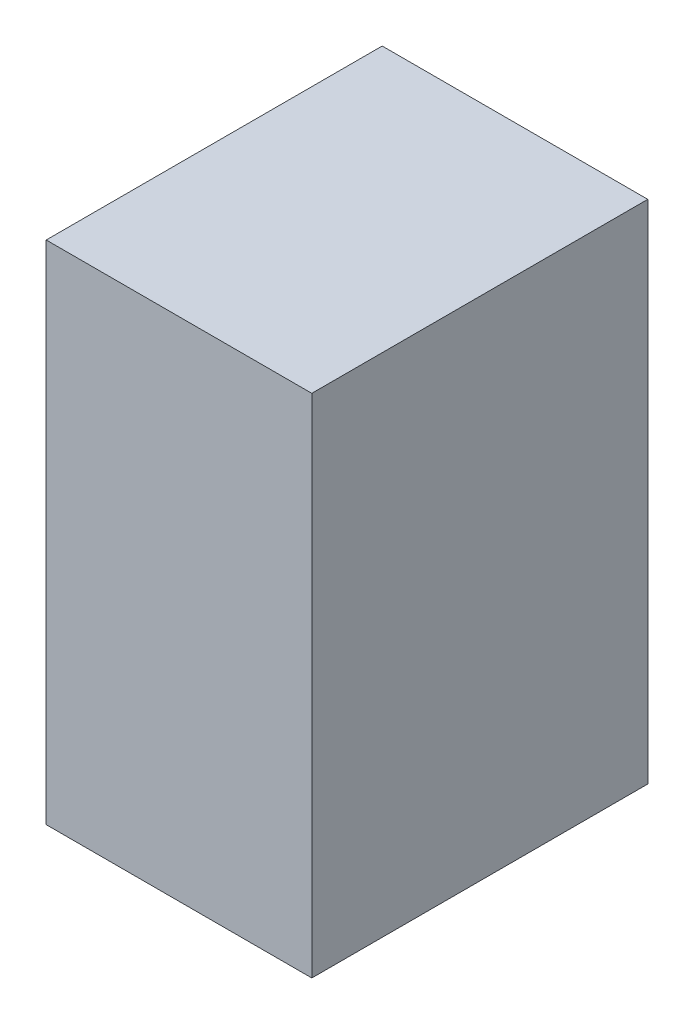
SolidWorks part; units mm, degrees
ref_plane "Front Plane" through (0, 0, 0) normal (0, 0, 1) x (1, 0, 0)
ref_plane "Top Plane" through (0, 0, 0) normal (0, 1, 0) x (1, 0, 0)
ref_plane "Right Plane" through (0, 0, 0) normal (1, 0, 0) x (0, 0, -1)
ref_plane "Plane1" through (0, 0, 110) normal (0, 0, 1) x (1, 0, 0)
ref_plane "Plane2" through (0, 0, 120) normal (0, 0, 1) x (1, 0, 0)
sketch "Sketch3" plane through (0, 0, 120) normal (0, 0, 1) x (1, 0, 0)
  line L5 (-655.6809, -1276.1699) -> (-694.681, -1276.1699) construction
  line L6 (-692.931, -1278.4199) -> (-657.431, -1278.4199) construction
  line L10 (-692.931, -1278.4199) -> (-692.931, -1326.9199) construction
  line L11 (-692.931, -1326.9199) -> (-657.431, -1326.9199) construction
  line L12 (-657.431, -1278.4199) -> (-657.431, -1326.9199) construction
  line L13 (-692.931, -1278.4199) -> (-657.431, -1326.9199) construction
  line L14 (-692.931, -1326.9199) -> (-657.431, -1278.4199) construction
  line L15 (-687.681, -1329.1699) -> (-662.681, -1329.1699)
  line L16 (-687.681, -1329.1699) -> (-687.681, -1276.1699)
  line L17 (-687.681, -1276.1699) -> (-662.681, -1276.1699)
  line L18 (-662.681, -1329.1699) -> (-662.681, -1276.1699)
  line L19 (-687.681, -1329.1699) -> (-662.681, -1276.1699) construction
  line L20 (-687.681, -1276.1699) -> (-662.681, -1329.1699) construction
  line L22 (-681.431, -1322.6699) -> (-668.931, -1322.6699)
  line L23 (-681.431, -1322.6699) -> (-681.431, -1282.6699)
  line L24 (-681.431, -1282.6699) -> (-668.931, -1282.6699)
  line L25 (-668.931, -1322.6699) -> (-668.931, -1282.6699)
  line L26 (-681.431, -1322.6699) -> (-668.931, -1282.6699) construction
  line L27 (-681.431, -1282.6699) -> (-668.931, -1322.6699) construction
  point P4 (-675.181, -1302.6699)
  point P7 (-675.181, -1302.6699)
  point P14 (-675.181, -1302.6699)
  dimension "D1" = 25
  dimension "D2" = 12.5
  dimension "D3" = 40
extrude "Boss-Extrude1" add sketch "Sketch3" against normal up to surface (120 mm away)
sketch "Sketch4" plane through (0, 0, 120) normal (0, 0, 1) x (1, 0, 0)
  line L0 (-675.181, -1329.1699) -> (-675.181, -1276.1699) construction
  line L1 (-687.681, -1329.1699) -> (-662.681, -1329.1699) construction
  line L2 (-662.681, -1276.1699) -> (-687.681, -1276.1699) construction
  line L3 (-662.681, -1302.6699) -> (-687.681, -1302.6699) construction
  line L4 (-662.681, -1329.1699) -> (-662.681, -1276.1699) construction
  line L5 (-687.681, -1276.1699) -> (-687.681, -1329.1699) construction
  line L6 (-696.431, -1323.4199) -> (-696.431, -1281.9199) construction
  line L7 (-633.931, -1256.1699) -> (-716.431, -1256.1699)
  line L8 (-633.931, -1256.1699) -> (-633.931, -1349.1699)
  line L9 (-633.931, -1349.1699) -> (-716.431, -1349.1699)
  line L10 (-716.431, -1256.1699) -> (-716.431, -1349.1699)
  line L11 (-633.931, -1256.1699) -> (-716.431, -1349.1699) construction
  line L12 (-633.931, -1349.1699) -> (-716.431, -1256.1699) construction
  point P12 (-675.181, -1302.6699)
  dimension "D1" = 20
  dimension "D2" = 20
extrude "Boss-Extrude2" add sketch "Sketch4" against normal blind 10
sketch "Sketch5" plane through (-687.681, 0, 0) normal (-1, 0, 0) x (0, 0, 1)
  line L8 (-3.81, -1276.1699) -> (0, -1276.1699)
  line L13 (-3.81, -1276.1699) -> (-3.81, -1271.1699)
  line L14 (0, -1272.1699) -> (0, -1271.1699)
  line L19 (-3.81, -1271.1699) -> (0, -1271.1699)
  line L20 (0, -1276.1699) -> (0, -1280.1699)
  line L21 (4, -1276.1699) -> (7.5, -1276.1699)
  line L25 (0, -1280.1699) -> (7.5, -1280.1699)
  line L26 (7.5, -1276.1699) -> (7.5, -1280.1699)
  line L27 (-6.25, -1302.6699) -> (13.6345, -1302.6699) construction
  line L28 (-6.25, -1289.5199) -> (-6.25, -1315.8199) construction
  line L29 (7.5, -1329.1699) -> (7.5, -1325.1699)
  line L30 (0, -1325.1699) -> (7.5, -1325.1699)
  line L31 (4, -1329.1699) -> (7.5, -1329.1699)
  line L32 (0, -1329.1699) -> (0, -1325.1699)
  line L33 (-3.81, -1334.1699) -> (0, -1334.1699)
  line L34 (0, -1333.1699) -> (0, -1334.1699)
  line L35 (-3.81, -1329.1699) -> (-3.81, -1334.1699)
  line L36 (-3.81, -1329.1699) -> (0, -1329.1699)
  arc A2 (4, -1276.1699) -> (0, -1272.1699) centre (4, -1272.1699) cw
  arc A3 (4, -1329.1699) -> (0, -1333.1699) centre (4, -1333.1699) ccw
  dimension "D2" = 7.5
  dimension "D3" = 5
  dimension "D1" = 4
extrude "Boss-Extrude3" add sketch "Sketch5" against normal up to surface (25 mm away) up to face at (-662.681, -1302.6699, 55)
sketch "Sketch6" plane through (-738.361, 0, 0) normal (-1, 0, 0) x (0, 0, 1)
  line L0 (120, -1256.1699) -> (120, -1349.1699) construction
  line L9 (120, -1256.1699) -> (120, -1349.1699)
  line L10 (120, -1256.1699) -> (-5, -1256.1699)
  line L11 (120, -1349.1699) -> (-5, -1349.1699)
  line L12 (-5, -1256.1699) -> (-5, -1349.1699)
  circle A0 centre (79.5065, -1302.8998) radius 32.5 construction
  circle A3 centre (79.5065, -1302.8998) radius 35
  dimension "D1" = 2.5
  dimension "D2" = 46.2701
  dimension "D4" = 70
  dimension "D3" = 40.4935
  dimension "D5" = 125
sketch "Sketch10" plane through (-687.681, 0, 0) normal (-1, 0, 0) x (0, 0, 1)
  circle A0 centre (0, -1329.1699) radius 0.5
  circle A1 centre (0, -1276.1699) radius 0.5
  dimension "D1" = 1
extrude "Cut-Extrude1" cut sketch "Sketch10" against normal through all both and the other way through all
sketch "Sketch11" plane through (0, -1256.1699, 0) normal (0, 1, 0) x (1, 0, 0)
  line L13 (-687.681, 3.81) -> (-662.681, 3.81)
  line L14 (-687.681, 3.81) -> (-687.681, 0)
  line L15 (-687.681, 0) -> (-662.681, 0)
  line L16 (-662.681, 3.81) -> (-662.681, 0)
  line L17 (-687.681, 3.81) -> (-662.681, 0) construction
  line L18 (-687.681, 0) -> (-662.681, 3.81) construction
  point P18 (-675.181, 1.905)
extrude "Boss-Extrude11" add sketch "Sketch11" against normal up to surface (15 mm away) up to face at (-675.181, -1271.1699, -1.905)
sketch "Sketch12" plane through (0, -1256.1699, 0) normal (0, 1, 0) x (1, 0, 0)
  line L1 (-710.761, 12.5) -> (-707.761, 12.5)
  line L2 (-710.761, 12.5) -> (-710.761, -30.4539)
  line L3 (-710.761, -30.4539) -> (-707.761, -30.4539)
  line L4 (-707.761, 12.5) -> (-707.761, -30.4539)
  line L5 (-710.761, 12.5) -> (-707.761, -30.4539) construction
  line L6 (-710.761, -30.4539) -> (-707.761, 12.5) construction
  line L7 (-642.6009, 12.5) -> (-639.6009, 12.5)
  line L8 (-642.6009, 12.5) -> (-642.6009, -25.4539)
  line L9 (-642.6009, -25.4539) -> (-639.6009, -25.4539)
  line L10 (-639.6009, 12.5) -> (-639.6009, -25.4539)
  line L11 (-642.6009, 12.5) -> (-639.6009, -25.4539) construction
  line L12 (-642.6009, -25.4539) -> (-639.6009, 12.5) construction
  point P4 (-709.261, -8.9769)
  point P11 (-641.1009, -6.4769)
extrude "Boss-Extrude12" add sketch "Sketch12" against normal up to surface (24 mm away) separate body
sketch "Sketch13" plane through (0, -1256.1699, 0) normal (0, 1, 0) x (1, 0, 0)
  line L0 (-652.1809, 30.41) -> (-698.1809, 30.41) construction
  line L1 (-695.2818, 35.57) -> (-655.0818, 35.57)
  line L2 (-695.2818, 35.57) -> (-695.2818, 30.41)
  line L3 (-695.2818, 30.41) -> (-655.0818, 30.41)
  line L4 (-655.0818, 35.57) -> (-655.0818, 30.41)
  line L5 (-695.2818, 35.57) -> (-655.0818, 30.41) construction
  line L6 (-695.2818, 30.41) -> (-655.0818, 35.57) construction
  point P4 (-675.1818, 32.99)
  dimension "D1" = 20.1
extrude "Boss-Extrude13" add sketch "Sketch13" against normal up to surface (10.4024 mm away) separate body
sketch "Sketch14" plane through (0, -1256.1699, 0) normal (0, 1, 0) x (1, 0, 0)
  line L0 (-716.431, -120) -> (-633.931, -120)
  line L1 (-716.431, -120) -> (-716.431, 35.5)
  line L2 (-633.931, -120) -> (-633.931, 35.5)
  line L3 (-716.431, 35.5) -> (-633.931, 35.5)
  dimension "D1" = 155.5
extrude "Boss-Extrude14" add sketch "Sketch14" against normal blind 5
sketch "Sketch15" plane through (-738.361, 0, 0) normal (-1, 0, 0) x (0, 0, 1)
  line L2 (120, -1349.1699) -> (-35.5, -1349.1699)
  line L3 (120, -1349.1699) -> (120, -1256.1699)
  line L4 (120, -1256.1699) -> (-35.5, -1256.1699)
  line L5 (-35.5, -1349.1699) -> (-35.5, -1256.1699)
  line L6 (120, -1349.1699) -> (-35.5, -1256.1699) construction
  line L7 (120, -1256.1699) -> (-35.5, -1349.1699) construction
  circle A0 centre (69.5065, -1302.44) radius 37.4
  circle A1 centre (69.5065, -1302.44) radius 30 construction
  point P9 (42.25, -1302.6699)
  dimension "D1" = 7.4
extrude "Boss-Extrude15" add sketch "Sketch15" along normal blind 20 separate body
sketch "Sketch16" plane through (-716.431, 0, 0) normal (-1, 0, 0) x (0, 0, 1)
  line L0 (110, -1349.1699) -> (120, -1349.1699)
  line L1 (120, -1349.1699) -> (120, -1256.1699)
  line L2 (120, -1256.1699) -> (-35.5, -1256.1699)
  line L3 (110, -1349.1699) -> (110, -1261.1699)
  line L4 (110, -1261.1699) -> (-35.5, -1261.1699)
  line L5 (-35.5, -1256.1699) -> (-35.5, -1349.1699) construction
  line L6 (-35.5, -1261.1699) -> (-35.5, -1256.1699)
  dimension "D1" = 5
extrude "Boss-Extrude16" add sketch "Sketch16" along normal up to surface (21.93 mm away) up to face at (-738.361, -1302.6699, 42.25)
extrude "Boss-Extrude4" add sketch "Sketch6" along normal blind 25 separate body
sketch "Sketch7" plane through (-103.987, 0, 0) normal (-1, 0, 0) x (0, 0, 1)
  line L1 (922.519, -46.7173) -> (120, -46.7173)
  line L2 (922.519, -46.7173) -> (922.519, -1256.1699)
  line L3 (922.519, -1256.1699) -> (120, -1256.1699)
  line L4 (120, -46.7173) -> (120, -1256.1699)
  line L5 (922.519, -46.7173) -> (120, -1256.1699) construction
  line L6 (922.519, -1256.1699) -> (120, -46.7173) construction
  point P4 (521.2595, -651.4436)
extrude "Boss-Extrude5" add sketch "Sketch7" along normal up to surface (634.3739 mm away) up to face at (-738.361, -1302.6699, 57.5)
sketch "Sketch9" plane through (0, -1266.5723, 0) normal (0, 1, 0) x (1, 0, 0)
  line L0 (-698.1809, 38.11) -> (-652.1809, 38.11)
  line L1 (-698.1809, 38.11) -> (-698.1809, -120)
  line L2 (-652.1809, 38.11) -> (-652.1809, -120)
  line L3 (-698.1809, -120) -> (-652.1809, -120)
  line L4 (-633.931, -120) -> (-758.361, -120) construction
extrude "Boss-Extrude7" add sketch "Sketch9" along normal up to surface (10.4024 mm away) up to face at (-421.174, -1256.1699, 521.2595)
